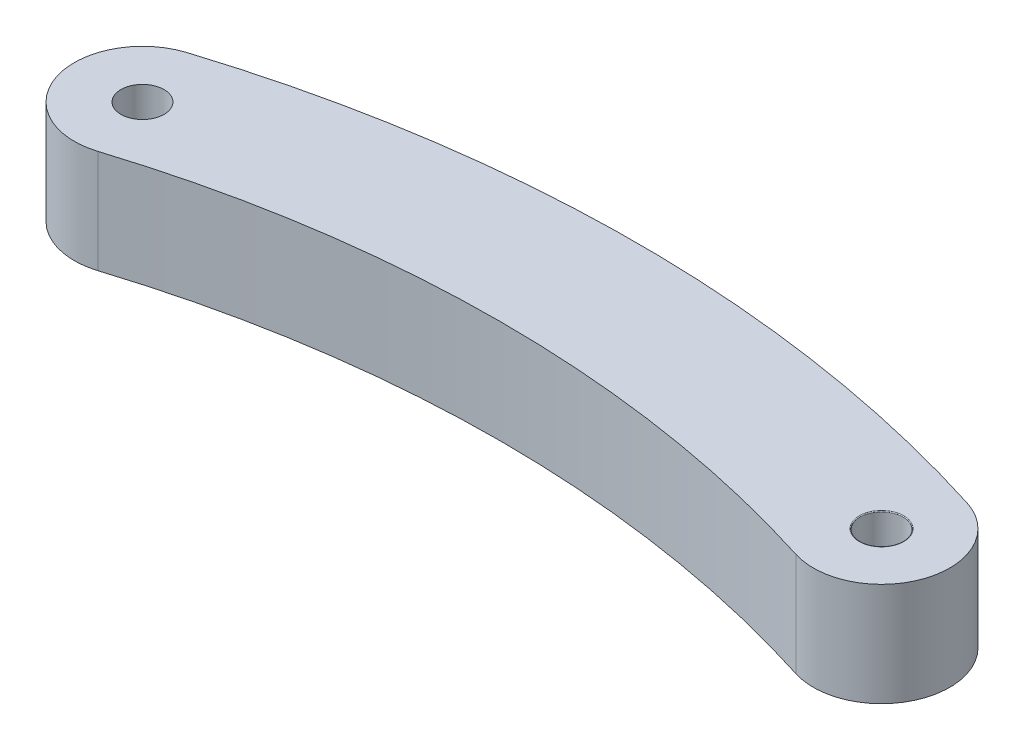
SolidWorks part; units mm, degrees
ref_plane "Front Plane" through (0, 0, 0) normal (0, 0, 1) x (1, 0, 0)
ref_plane "Top Plane" through (0, 0, 0) normal (0, 1, 0) x (1, 0, 0)
ref_plane "Right Plane" through (0, 0, 0) normal (1, 0, 0) x (0, 0, -1)
sketch "Sketch1" plane through (0, 0, 0) normal (0, 1, 0) x (1, 0, 0)
  line L0 (-45.5978, -4.8805) -> (45.2072, -4.8805)
  line L1 (-45.5978, -13.2605) -> (42.1253, -13.2605)
  circle A0 centre (45.2072, -4.8805) radius 2.65
  circle A1 centre (-45.5978, -4.8805) radius 2.65
  circle A2 centre (45.2072, -4.8805) radius 37.25
  circle A3 centre (-45.5978, -4.8805) radius 8.38
  circle A4 centre (45.2072, -4.8805) radius 8.38
  arc A5 (-43.0738, -12.8713) -> (42.6832, -12.8713) centre (-0.1953, -148.6224) cw
  arc A6 (-48.1218, 3.1104) -> (47.7312, 3.1104) centre (-0.1953, -148.6224) cw
  point P5 (0, 0)
  point P15 (-0.1953, -6.2605)
  point P16 (-0.1953, 10.4995)
  dimension "D1" = 5.3
  dimension "D2" = 5.3
  dimension "D4" = 74.5
  dimension "D6" = 16.76
  dimension "D7" = 16.76
  dimension "D8" = 16.76
  dimension "D3" = 90.805
  dimension "D5" = 7
extrude "Boss-Extrude1" add sketch "Sketch1" along normal blind 12.7
fillet "Fillet1" radius 0.1 1 edges at (45.2072, 12.7, 7.5305)
